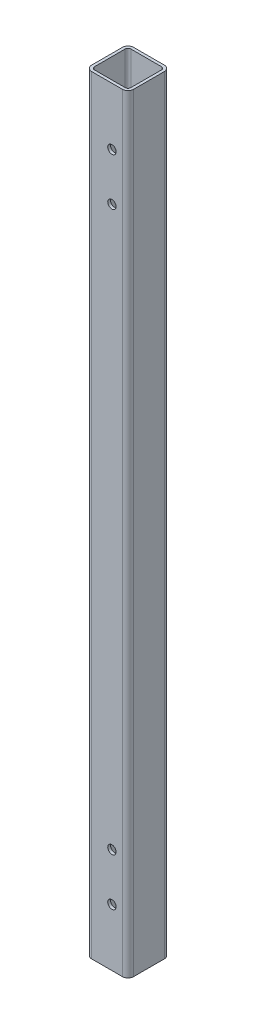
SolidWorks part; units mm, degrees
material "AISI 1010 钢，热轧条材"
ref_plane "前视基准面" through (0, 0, 0) normal (0, 0, 1) x (1, 0, 0)
ref_plane "上视基准面" through (0, 0, 0) normal (0, 1, 0) x (1, 0, 0)
ref_plane "右视基准面" through (0, 0, 0) normal (1, 0, 0) x (0, 0, -1)
sketch "草图1" plane through (0, 0, 0) normal (0, 1, 0) x (1, 0, 0)
  line L0 (-11, -13) -> (11, -13)
  line L1 (-11, -15) -> (11, -15)
  line L2 (-15, -11) -> (-15, 11)
  line L3 (-11, 15) -> (11, 15)
  line L4 (15, -11) -> (15, 11)
  line L5 (13, -11) -> (13, 11)
  line L6 (-11, 13) -> (11, 13)
  line L7 (-13, -11) -> (-13, 11)
  arc A0 (-11, -15) -> (-15, -11) centre (-11, -11) cw
  arc A1 (11, -15) -> (15, -11) centre (11, -11) ccw
  arc A2 (11, 15) -> (15, 11) centre (11, 11) cw
  arc A3 (-15, 11) -> (-11, 15) centre (-11, 11) cw
  arc A4 (11, -13) -> (13, -11) centre (11, -11) ccw
  arc A5 (11, 13) -> (13, 11) centre (11, 11) cw
  arc A6 (-13, 11) -> (-11, 13) centre (-11, 11) cw
  arc A7 (-11, -13) -> (-13, -11) centre (-11, -11) cw
extrude "凸台-拉伸1" add sketch "草图1" along normal mid plane 550
sketch "草图2" plane through (0, 0, 0) normal (0, 0, 1) x (1, 0, 0)
  line L0 (14.3201, 0) -> (-15, 0) construction
  line L1 (-15, 275) -> (-15, -275) construction
  circle A0 centre (3.5, 233.9694) radius 3
  circle A1 centre (3.5, 199.9694) radius 3
  circle A2 centre (3.5, -199.9694) radius 3
  circle A3 centre (3.5, -233.9694) radius 3
  dimension "D1" = 6
  dimension "D2" = 34
  dimension "D3" = 200
  dimension "D4" = 18.5
extrude "切除-拉伸1" cut sketch "草图2" against normal through all both and the other way through all
